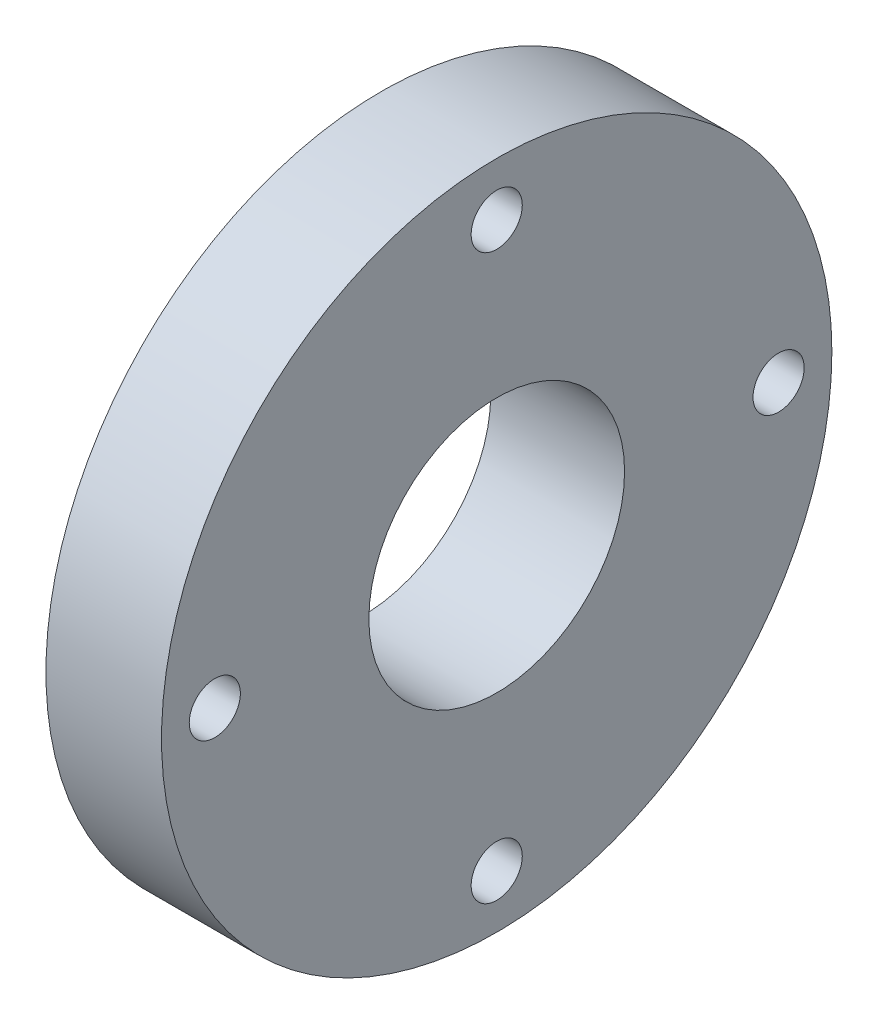
SolidWorks part; units mm, degrees
ref_plane "Front Plane" through (0, 0, 0) normal (0, 0, 1) x (1, 0, 0)
ref_plane "Top Plane" through (0, 0, 0) normal (0, 1, 0) x (1, 0, 0)
ref_plane "Right Plane" through (0, 0, 0) normal (1, 0, 0) x (0, 0, -1)
sketch "Sketch1" plane through (0, 0, 0) normal (1, 0, 0) x (0, 0, -1)
  circle A0 centre (0, 0) radius 32.766
  dimension "D1" = 65.532
extrude "Boss-Extrude1" add sketch "Sketch1" against normal blind 11.303
sketch "Sketch2" plane through (-11.303, 0, 0) normal (-1, 0, 0) x (0, 0, 1)
  circle A0 centre (0, 0) radius 22.479
  dimension "D1" = 44.958
extrude "Boss-Extrude2" add sketch "Sketch2" along normal blind 1.778
sketch "Sketch3" plane through (-13.081, 0, 0) normal (-1, 0, 0) x (0, 0, 1)
  circle A0 centre (0, 0) radius 12.5
  dimension "D1" = 25
extrude "Cut-Extrude1" cut sketch "Sketch3" against normal through all
sketch "Sketch5" plane through (-11.303, 0, 0) normal (-1, 0, 0) x (0, 0, 1)
  circle A0 centre (0, 0) radius 27.559 construction
  dimension "D1" = 55.118
hole_wizard "M6 Tapped Hole1" positions "Sketch7" profile "Sketch6" tap size "M6" standard "DIN"
sketch "Sketch7" plane through (-11.303, 0, 0) normal (-1, 0, 0) x (0, 0, 1)
  circle A0 centre (0, 0) radius 27.559 construction
  point P0 (0, 27.559)
  point P4 (27.559, 0)
  point P6 (0, -27.559)
  point P8 (-27.559, 0)
sketch "Sketch6" plane through (-11.303, 27.559, 0) normal (0, 1, 0) x (0, 0, 1)
  line L0 (0, 0) -> (0, 13.9482)
  line L1 (0, 13.9482) -> (2.5, 12.446)
  line L2 (2.5, 12.446) -> (2.5, 0)
  line L5 (2.5, 0) -> (0, 0)
  line L10 (0, 13.9482) -> (-2.5, 12.446) construction
  line L11 (0, -6.35) -> (0, 107.95) construction
  dimension "Tap Drill Dia." = 5
  dimension "Tap Drill Depth" = 12.446
  dimension "Drill Angle" = 118
cosmetic thread "Hole Thread1" parameters "D1"=9.398, "D2"=6
cosmetic thread "Hole Thread2" parameters "D1"=9.398, "D2"=6
cosmetic thread "Hole Thread3" parameters "D1"=9.398, "D2"=6
cosmetic thread "Hole Thread4" parameters "D1"=9.398, "D2"=6
